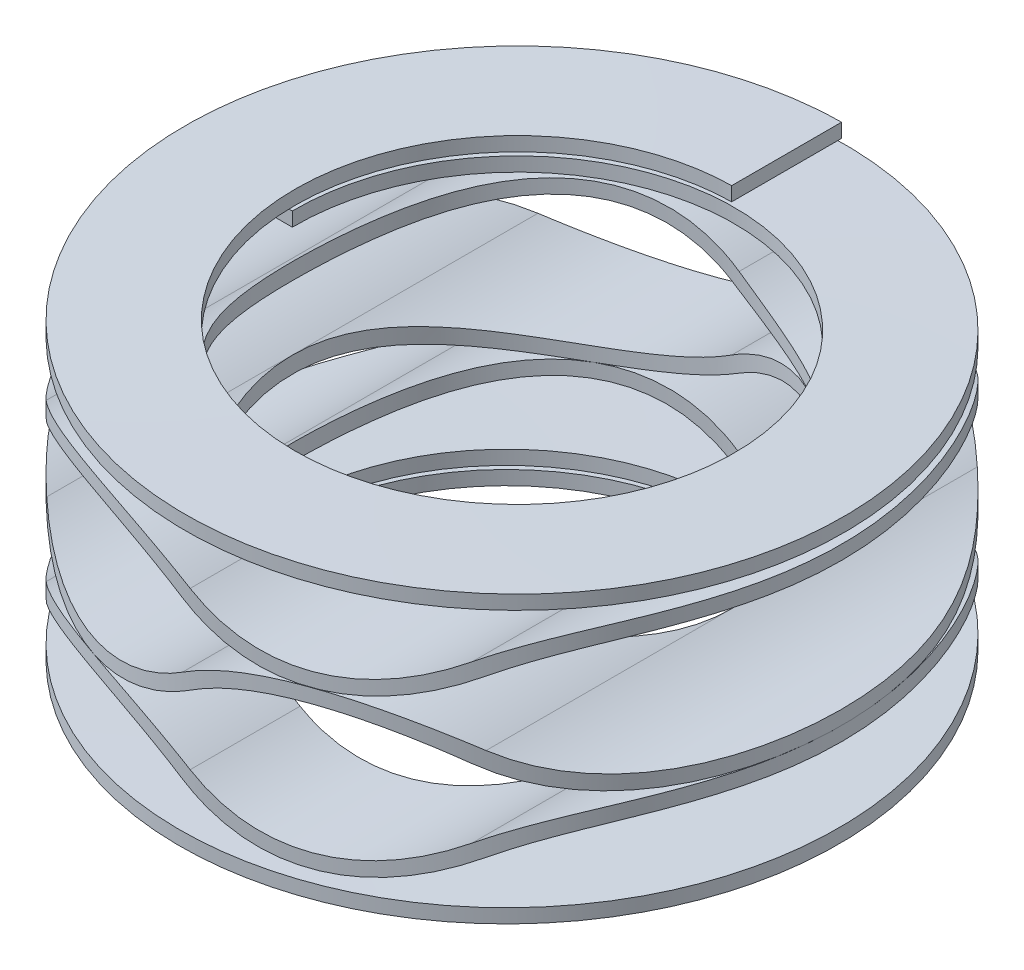
SolidWorks part; units mm, degrees
ref_plane "Front Plane" through (0, 0, 0) normal (0, 0, 1) x (1, 0, 0)
ref_plane "Top Plane" through (0, 0, 0) normal (0, 1, 0) x (1, 0, 0)
ref_plane "Right Plane" through (0, 0, 0) normal (1, 0, 0) x (0, 0, -1)
sketch "Sketch1" plane through (0, 0, 0) normal (0, 1, 0) x (1, 0, 0)
  line L0 (-4.7625, 0) -> (58.7375, 0) construction
  line L1 (3.175, 0) -> (4.7625, 0) construction
  circle A0 centre (0, 0) radius 3.175
  circle A1 centre (0, 0) radius 4.7625
  point P6 (-3.175, 0)
  point P7 (3.175, 0)
  point P8 (4.7625, 0)
  point P11 (3.9688, 0)
  dimension "Number of Waves" = 63.5
sketch "Sketch2" plane through (0, 0, 0) normal (0, 0, 1) x (1, 0, 0)
  line L0 (0, 1.905) -> (0, -1.905) construction
  line L1 (4.7625, 0) -> (-4.7625, 0) construction
  line L2 (-4.7625, -1.905) -> (-4.7625, -1.7018) construction
  point P3 (-4.7625, 1.905)
  point P4 (0, 1.905)
  point P8 (1.6498, -0.9525)
  point P9 (-1.6498, -0.9525)
  point P11 (0, 0)
  point P18 (-4.7625, -1.8034)
  dimension "Height" = 3.81
  dimension "Thickness" = 0.2032
  dimension "Number of Turns" = 3
sketch "Sketch3" plane through (0, 0, 0) normal (0, 0, 1) x (1, 0, 0)
  line L0 (0, -1.905) -> (0, -0.5673) construction
  line L1 (0, 1.905) -> (0, -1.905) construction
  line L2 (-4.7625, -1.905) -> (-1.5875, -1.905) construction
  line L3 (0, -0.5673) -> (-4.7625, -0.5673) construction
  line L4 (-4.7625, -0.7705) -> (0, -0.7705) construction
  line L5 (-1.5875, -1.905) -> (-1.5875, -0.7705) construction
  line L6 (-4.7625, -1.7018) -> (-1.5875, -1.7018) construction
  arc A0 (-4.7625, -1.7018) -> (-3.175, -1.2361) centre (-4.7625, 1.237) ccw
  arc A1 (-3.175, -1.2361) -> (-1.5875, -0.7705) centre (-1.5875, -3.7093) cw
  dimension "D2" = 3.175
  dimension "D3" = 0.2032
  dimension "D1" = 1.1345
surface "Surface-Extrude1" sketch "Sketch3" parameters "D1"=9.525
ref_plane "Plane1" through (-1.5875, 0, 0) normal (1, 0, 0) x (0, 0, -1)
mirror "Mirror1" about plane through (-1.5875, 0, 0) normal (1, 0, 0)
ref_plane "Plane2" through (1.5875, 0, 0) normal (1, 0, 0) x (0, 0, -1)
mirror "Mirror2" about plane through (1.5875, 0, 0) normal (1, 0, 0)
surface "Surface-Knit1"
thicken "Thicken1" surfaces to thicken 107 thickness 0.2032 parameters "D1"=0.2032
ref_plane "Plane3" through (0, -0.5673, 0) normal (0, 1, 0) x (-1, 0, 0)
mirror "Mirror3" about plane through (0, -0.5673, 0) normal (0, 1, 0) of bodies 108
pattern_linear "LPattern1" count 3 spacing 2.2691 along (0, 1, 0) of bodies 108 109
sketch "Sketch4" plane through (0, 0, 0) normal (0, 1, 0) x (1, 0, 0)
  circle A0 centre (0, 0) radius 4.7625 construction
  circle A1 centre (0, 0) radius 4.7625
extrude "Cut-Extrude1" cut sketch "Sketch4" against normal through all both and the other way through all flip side to cut
sketch "Sketch5" plane through (0, 0, 0) normal (0, 1, 0) x (1, 0, 0)
  circle A0 centre (0, 0) radius 3.175 construction
  circle A1 centre (0, 0) radius 3.175
extrude "Cut-Extrude2" cut sketch "Sketch5" against normal through all both and the other way through all
sketch "Sketch6" plane through (0, 0, 0) normal (0, 0, 1) x (1, 0, 0)
  line L0 (0, 1.905) -> (0, -1.905) construction
  line L5 (4.7625, 1.7018) -> (-4.7625, 1.7018)
  line L6 (4.7625, 1.7018) -> (4.7625, -1.7018)
  line L7 (4.7625, -1.7018) -> (-4.7625, -1.7018)
  line L8 (-4.7625, 1.7018) -> (-4.7625, -1.7018)
  line L9 (0, -1.7018) -> (0, 1.7018) construction
  line L10 (4.7625, 0) -> (-4.7625, 0) construction
  point P0 (0, 0)
extrude "Cut-Extrude3" cut sketch "Sketch6" against normal through all both and the other way through all flip side to cut
ref_plane "Plane4" through (0, -1.8034, 0) normal (0, 1, 0) x (1, 0, 0)
sketch "Sketch7" plane through (0, -1.8034, 0) normal (0, 1, 0) x (1, 0, 0)
  circle A0 centre (0, 0) radius 3.9688
curve "Helix/Spiral1" pitch 0.254 height 0.3175 turns 1.25
sketch "Sketch8" plane through (0, 0, 0) normal (0, 0, 1) x (1, 0, 0)
  line L4 (-4.7625, -1.905) -> (-4.7625, -1.7018)
  line L5 (-4.7625, -1.7018) -> (-3.175, -1.7018)
  line L6 (-3.175, -1.7018) -> (-3.175, -1.905)
  line L7 (-3.175, -1.905) -> (-4.7625, -1.905)
  line L10 (0, 1.905) -> (0, -1.905) construction
  point P9 (-3.175, 0)
sweep "Sweep1" add profiles "Sketch8" path "Helix/Spiral1"
mirror "Mirror4" about plane through (0, 0, 0) normal (0, 1, 0) of bodies 171
equation "\"D2@Sketch3\" = \"For Hole Diameter@Sketch1\" /  ( \"Number of Waves@Sketch1\" + 0.5 ) "
equation "\"D3@Sketch3\" = \"Thickness@Sketch2\""
equation "\"D1@Thicken1\" = \"Thickness@Sketch2\""
equation "\"D1@LPattern1\" = \"Number of Turns@Sketch2\" / 2 + 1"
equation "\"D3@LPattern1\" =  (  ( \"Height@Sketch2\" - \"Thickness@Sketch2\" * 2 )  / \"Number of Turns@Sketch2\" )  * 2"
equation "\"D1@Sketch3\" =  ( \"Height@Sketch2\" - \"Thickness@Sketch2\" * 2 )  / \"Number of Turns@Sketch2\""
equation "\"D1@Surface-Extrude1\" = \"For Hole Diameter@Sketch1\""
equation "\"D4@Helix/Spiral1\"=\"Thickness@Sketch2\" + (\"Thickness@Sketch2\")*.25"
equation "\"D3@Helix/Spiral1\" = \"Thickness@Sketch2\" + .1"
